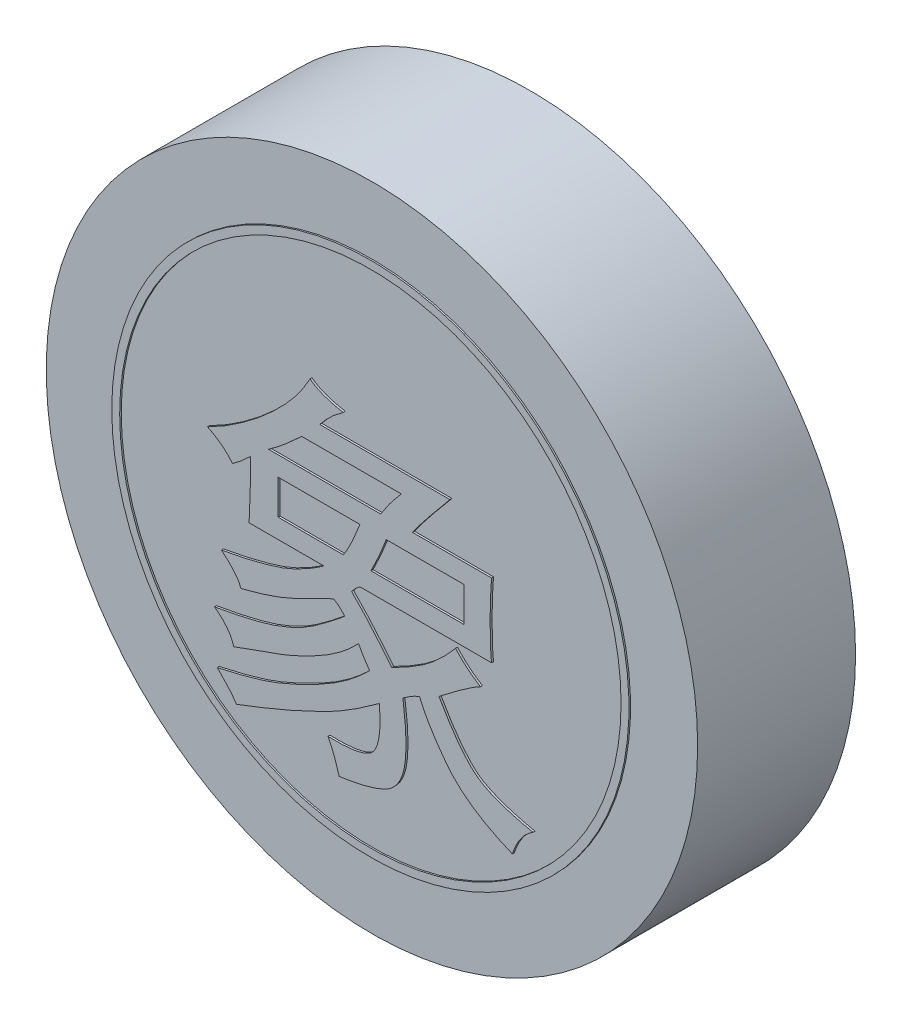
SolidWorks part; units mm, degrees
ref_plane "前视基准面" through (0, 0, 0) normal (0, 0, 1) x (1, 0, 0)
ref_plane "上视基准面" through (0, 0, 0) normal (0, 1, 0) x (1, 0, 0)
ref_plane "右视基准面" through (0, 0, 0) normal (1, 0, 0) x (0, 0, -1)
other "Configuration Table"
sketch "草图1" plane through (0, 0, 0) normal (0, 0, 1) x (1, 0, 0)
  circle A0 centre (0, 0) radius 16.5
  dimension "D1" = 33
extrude "Diameter33_Height8" add sketch "草图1" against normal blind 8
sketch "草图2" plane through (0, 0, 0) normal (0, 0, 1) x (1, 0, 0)
  text T0 "象" font "SimHei" height 12
extrude "Character_象" add sketch "草图2" along normal blind 0.1
sketch "草图3" plane through (0, 0, 0) normal (0, 0, 1) x (1, 0, 0)
  circle A0 centre (0, 0) radius 13.1
  circle A1 centre (0, 0) radius 12.7
extrude "Ink_ring" add sketch "草图3" along normal blind 0.08
